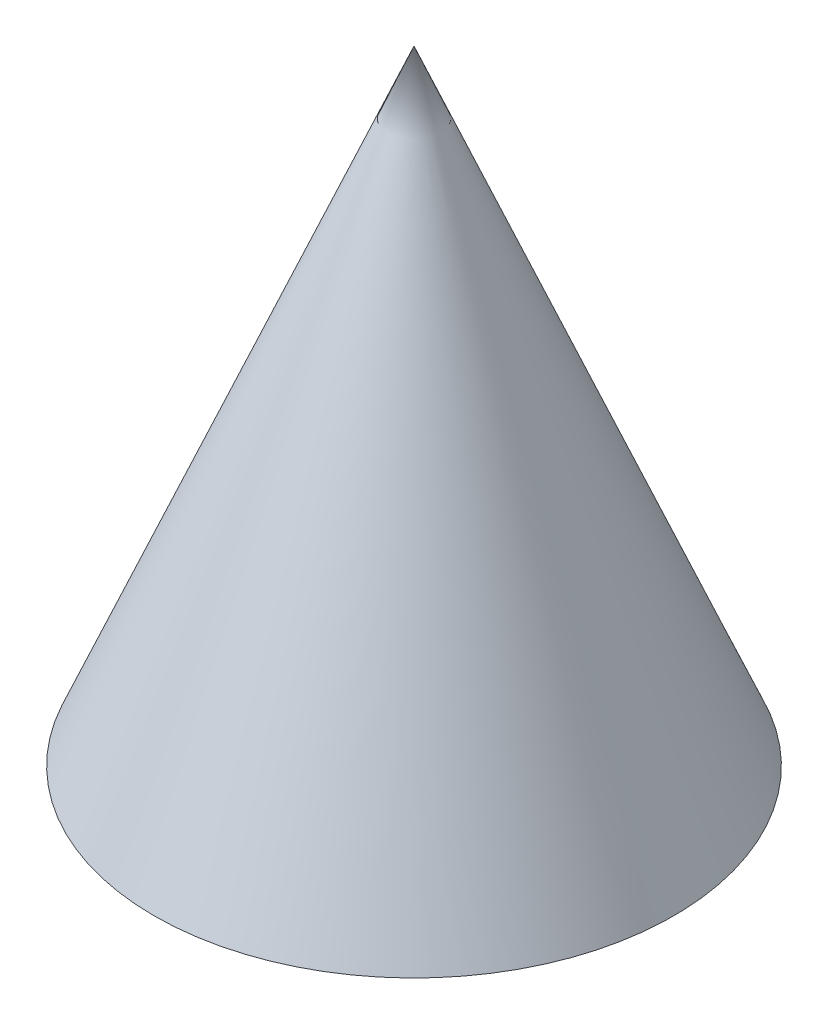
SolidWorks part; units mm, degrees
ref_plane "Alzado" through (0, 0, 0) normal (0, 0, 1) x (1, 0, 0)
ref_plane "Planta" through (0, 0, 0) normal (0, 1, 0) x (1, 0, 0)
ref_plane "Vista lateral" through (0, 0, 0) normal (1, 0, 0) x (0, 0, -1)
sketch "Croquis_perfil" plane through (0, 0, 0) normal (0, 0, 1) x (1, 0, 0)
  line L0 (0, 0) -> (0, 120) construction
  line L1 (0, 0) -> (50, 0)
  line L2 (50, 0) -> (0, 120)
  line L3 (0, 120) -> (0, 0)
  dimension "D1" = 50
  dimension "D2" = 120
revolve "Cono_D100x120" add sketch "Croquis_perfil" angle 360 about L0
sketch "Croquis_agujeros_montaje" plane through (0, 0, 0) normal (0, 1, 0) x (1, 0, 0)
  circle A0 centre (0, 0) radius 4
  dimension "D1" = 8
extrude "Agujero_inserto_M6" cut sketch "Croquis_agujeros_montaje" along normal blind 14
